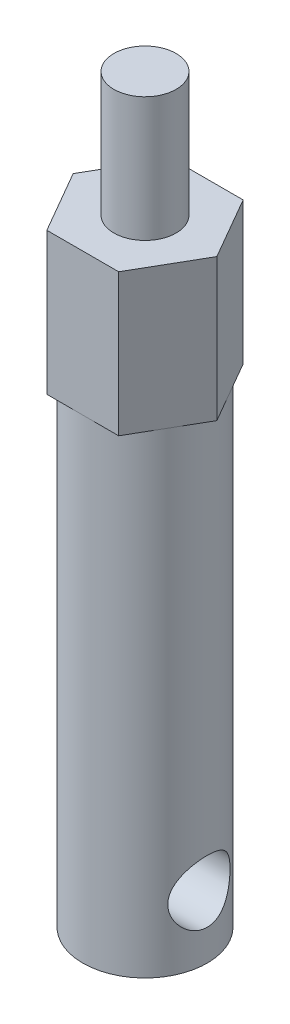
SolidWorks part; units mm, degrees
material "AISI 316 Annealed Stainless Steel Bar (SS)"
ref_plane "Front Plane" through (0, 0, 0) normal (0, 0, 1) x (1, 0, 0)
ref_plane "Top Plane" through (0, 0, 0) normal (0, 1, 0) x (1, 0, 0)
ref_plane "Right Plane" through (0, 0, 0) normal (1, 0, 0) x (0, 0, -1)
sketch "Sketch1" plane through (0, 0, 0) normal (0, 1, 0) x (1, 0, 0)
  circle A1 centre (0, 0) radius 6.35
  dimension "D1" = 12.7
extrude "Boss-Extrude1" add sketch "Sketch1" along normal blind 48.4442
sketch "Sketch2" plane through (0, 48.4442, 0) normal (0, 1, 0) x (1, 0, 0)
  line L1 (7.3323, 0) -> (3.6662, 6.35)
  line L2 (3.6662, 6.35) -> (-3.6662, 6.35)
  line L3 (-3.6662, 6.35) -> (-7.3323, 0)
  line L4 (-7.3323, 0) -> (-3.6662, -6.35)
  line L5 (-3.6662, -6.35) -> (3.6662, -6.35)
  line L6 (3.6662, -6.35) -> (7.3323, 0)
  circle A0 centre (0, 0) radius 6.35 construction
  dimension "D1" = 12.7
extrude "Boss-Extrude2" add sketch "Sketch2" along normal blind 14.5
sketch "Sketch4" plane through (0, 0, 0) normal (1, 0, 0) x (0, 0, -1)
  line L0 (-6.35, 0) -> (6.35, 0) construction
  line L1 (6.35, 0) -> (6.35, 48.4442) construction
  circle A0 centre (0, 6.35) radius 3.175
  dimension "D1" = 6.35
  dimension "D2" = 6.35
  dimension "D3" = 6.35
extrude "Cut-Extrude1" cut sketch "Sketch4" against normal through all and the other way through all
sketch "Sketch5" plane through (0, 62.9441, 0) normal (0, 1, 0) x (1, 0, 0)
  circle A0 centre (0, 0) radius 3.175
  dimension "D1" = 6.35
extrude "Boss-Extrude3" add sketch "Sketch5" along normal blind 12.7
thread "Thread1" pitch 1.27 start angle 0, offset 0, length 0, pitch 1.27, diameter 6.35
ref_plane "Plane1" through (-3.175, 80.6008, 0) normal (0, 0, 1) x (-1, 0, 0)
sketch "Thread Profile1" plane through (-3.175, 80.6008, 0) normal (0, 0, 1) x (-1, 0, 0)
  line L0 (0, 0) -> (0, 1.27) construction
  line L11 (0, 0) -> (0, 1.1112)
  line L12 (0, 1.1112) -> (-0.6874, 0.7144)
  line L13 (-0.6874, 0.7144) -> (-0.6874, 0.3969)
  line L15 (-0.6874, 0.3969) -> (0, 0)
  line L17 (-0.6874, 0.5556) -> (0, 0.5556) construction
  point P2 (0, 0)
  dimension "Pitch" = 1.27
  dimension "Profile_Angle" = 60
  dimension "Profile_Land" = 0.3175
  dimension "Profile_Height" = 0.6874
